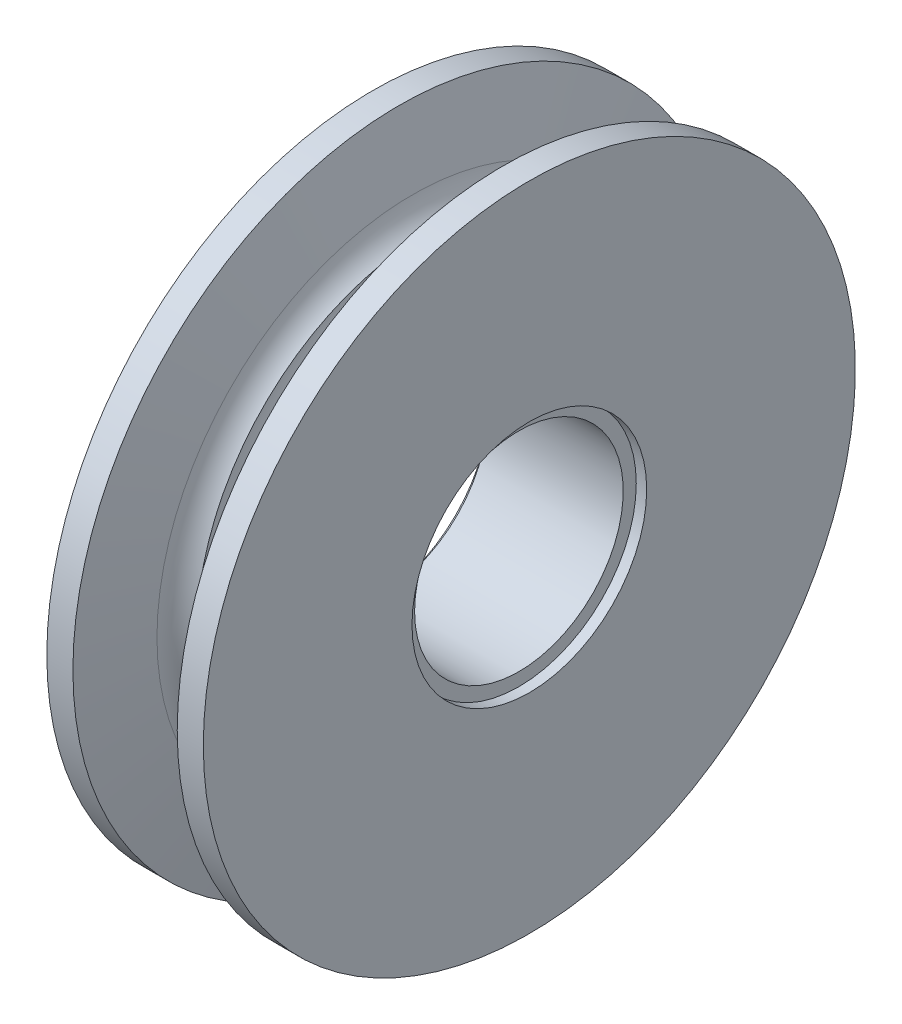
SolidWorks part; units mm, degrees
ref_plane "Спереди" through (0, 0, 0) normal (0, 0, 1) x (1, 0, 0)
ref_plane "Сверху" through (0, 0, 0) normal (0, 1, 0) x (1, 0, 0)
ref_plane "Справа" through (0, 0, 0) normal (1, 0, 0) x (0, 0, -1)
sketch "Эскиз1" plane through (0, 0, 0) normal (0, 0, 1) x (1, 0, 0)
  line L0 (-4, 26.3846) -> (-4, -27.5664) construction
  line L1 (4, 26.3846) -> (4, -27.5664) construction
  line L2 (-8.1146, 16) -> (7.3584, 16) construction
  line L3 (0, 15.2069) -> (0, 0.6915) construction
  line L4 (-6.4331, 17.75) -> (7.3584, 17.75) construction
  line L5 (-4, 25) -> (-2.944, 19.6099)
  line L6 (-4, 25) -> (-6, 25)
  line L7 (4, 25) -> (2.944, 19.6099)
  line L8 (-6, 25) -> (-6, 0)
  line L9 (-6, 0) -> (6, 0)
  line L10 (-6.0596, 25) -> (6.7697, 25) construction
  line L11 (6, 0) -> (6, 25)
  line L12 (6, 25) -> (4, 25)
  arc A0 (-1.75, 17.75) -> (1.75, 17.75) centre (0, 17.75) ccw
  arc A1 (-2.944, 19.6099) -> (-1.75, 17.75) centre (0, 20.1867) ccw
  arc A2 (1.75, 17.75) -> (2.944, 19.6099) centre (0, 20.1867) ccw
  point P14 (1.75, 17.75)
  dimension "D1" = 3.5
  dimension "D2" = 6
  dimension "D3" = 9
  dimension "D4" = 12
  dimension "D5" = 6
  dimension "D6" = 2
  dimension "D7" = 2
  dimension "D8" = 25
revolve "Повернуть1" add sketch "Эскиз1" angle 360 about L9
sketch "Эскиз4" plane through (-6, 0, 0) normal (-1, 0, 0) x (0, 0, 1)
  circle A0 centre (0, 0) radius 8
  dimension "D1" = 16
extrude "Вырез-Вытянуть1" cut sketch "Эскиз4" against normal through all
sketch "Эскиз5" plane through (-6, 0, 0) normal (-1, 0, 0) x (0, 0, 1)
  circle A0 centre (0, 0) radius 9
  dimension "D1" = 18
extrude "Вырез-Вытянуть2" cut sketch "Эскиз5" against normal blind 0.8
mirror "Зеркальное отражение1" about plane through (0, 0, 0) normal (1, 0, 0) of "Вырез-Вытянуть2"
hole_wizard "Отверстие с зазором M51" positions "Эскиз7" profile "Эскиз6" hole size "M5" standard "Ansi Metric"
sketch "Эскиз7" plane through (6, 0, 0) normal (1, 0, 0) x (0, 0, -1)
  point P0 (9.1752, 18.9051)
sketch "Эскиз6" plane through (6, 18.9051, -9.1752) normal (0, 1, 0) x (0, 0, -1)
  line L0 (0, 0) -> (0, 12)
  line L1 (0, 12) -> (2.75, 12)
  line L2 (2.75, 12) -> (2.75, 0)
  line L5 (2.75, 0) -> (0, 0)
  line L11 (0, -6.35) -> (0, 107.95) construction
  dimension "Диаметр сквозного отверстия" = 5.5
  dimension "Глубина сквозного отверстия" = 12
